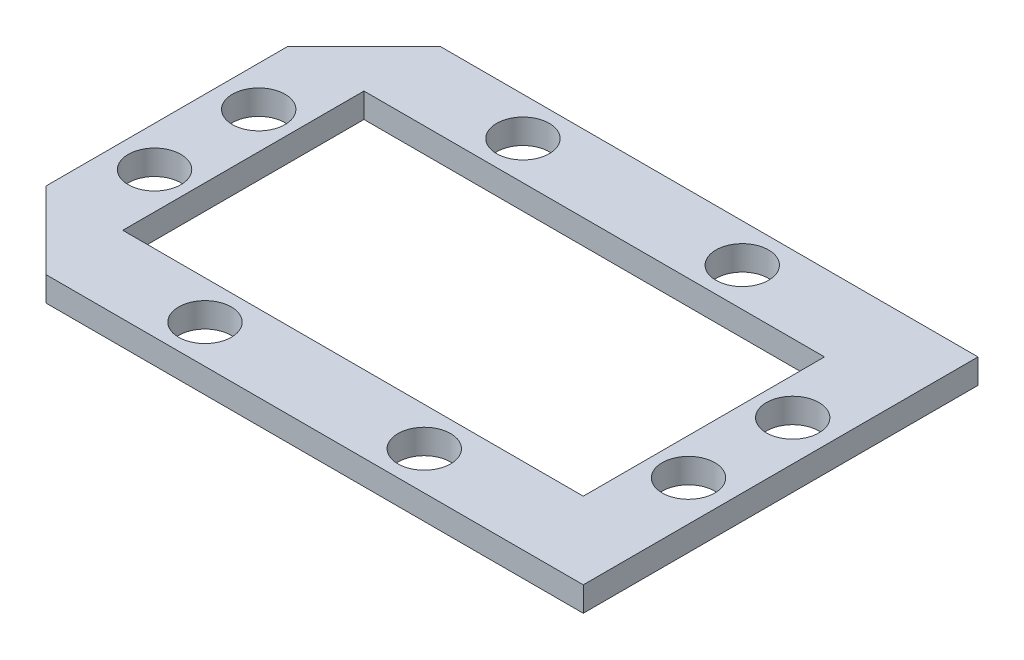
SolidWorks part; units mm, degrees
ref_plane "Front Plane" through (0, 0, 0) normal (0, 0, 1) x (1, 0, 0)
ref_plane "Top Plane" through (0, 0, 0) normal (0, 1, 0) x (1, 0, 0)
ref_plane "Right Plane" through (0, 0, 0) normal (1, 0, 0) x (0, 0, -1)
sketch "Sketch1" plane through (0, 0, 0) normal (0, 1, 0) x (1, 0, 0)
  line L0 (-24.35, 0) -> (24.35, 0) construction
  line L6 (-28, 18) -> (28, 18)
  line L7 (-21, 11) -> (21, 11)
  line L8 (-21, 11) -> (-21, -11)
  line L9 (-21, -11) -> (21, -11)
  line L10 (21, 11) -> (21, -11)
  line L11 (-21, 11) -> (21, -11) construction
  line L12 (-21, -11) -> (21, 11) construction
  line L13 (-24.35, 9.5) -> (24.35, 9.5)
  line L14 (-24.35, 9.5) -> (-24.35, -9.5)
  line L15 (-24.35, -9.5) -> (24.35, -9.5)
  line L16 (24.35, 9.5) -> (24.35, -9.5)
  line L17 (-24.35, 9.5) -> (24.35, -9.5) construction
  line L18 (-24.35, -9.5) -> (24.35, 9.5) construction
  line L19 (0, 0) -> (0, 9.5) construction
  line L20 (0, 0) -> (0, -9.5) construction
  line L21 (-24.35, -4.75) -> (24.35, -4.75) construction
  line L22 (-28, 18) -> (-28, -18)
  line L23 (-28, -18) -> (28, -18)
  line L24 (24.35, 4.75) -> (-24.35, 4.75) construction
  line L25 (28, 18) -> (28, -18)
  line L26 (-28, 18) -> (28, -18) construction
  line L27 (-28, -18) -> (28, 18) construction
  line L28 (-10, 14.5) -> (10, 14.5)
  line L29 (-10, 14.5) -> (-10, -14.5)
  line L30 (-10, -14.5) -> (10, -14.5)
  line L31 (10, 14.5) -> (10, -14.5)
  line L32 (-10, 14.5) -> (10, -14.5) construction
  line L33 (-10, -14.5) -> (10, 14.5) construction
  circle A0 centre (24.35, -4.75) radius 2.4
  circle A1 centre (24.35, 4.75) radius 2.4
  circle A2 centre (-24.35, -4.75) radius 2.4
  circle A3 centre (-24.35, 4.75) radius 2.4
  circle A5 centre (10, 14.5) radius 2.4
  circle A6 centre (10, -14.5) radius 2.4
  circle A7 centre (-10, -14.5) radius 2.4
  circle A8 centre (-10, 14.5) radius 2.4
  point P0 (0, 0)
  point P1 (0, 0)
  point P6 (0, 0)
  point P8 (0, 0)
  point P24 (0, -4.75)
  point P31 (0, 0)
  point P38 (0, 4.75)
  dimension "D3" = 4.8
  dimension "D4" = 4.8
  dimension "D5" = 4.8
  dimension "D6" = 4.8
  dimension "D13" = 4.8
  dimension "D14" = 4.8
  dimension "D15" = 4.8
  dimension "D16" = 4.8
  dimension "D1" = 48.7
  dimension "D2" = 19
  dimension "D7" = 42
  dimension "D8" = 22
  dimension "D9" = 36
  dimension "D10" = 56
  dimension "D11" = 29
  dimension "D12" = 20
extrude "Boss-Extrude1" add sketch "Sketch1" along normal blind 2.25 contours L25 L6 L22 L23 A8 L28 A5 L31 L7 L10 L13 L16 A1 A0 L15 L9 A6 L30 A7 L29 L8 L14 A2 A3 | A3 L14 A2 L15 L8 L13 | A7 L30 A6 L31 L9 L29 | A8 L29 L7 L31 A5 L28 | A1 L16 L13 L10 L15 A0
sketch "Sketch2" plane through (0, 2.25, 0) normal (0, 1, 0) x (1, 0, 0)
  line L0 (-21, 18) -> (-28, 11)
  line L10 (-28, -11) -> (-21, -11)
  line L11 (-28, -11) -> (-28, -18)
  line L12 (-28, -18) -> (-21, -18)
  line L13 (-21, -11) -> (-21, -18)
  line L14 (-28, -11) -> (-21, -18) construction
  line L15 (-28, -18) -> (-21, -11) construction
  line L16 (-28, 18) -> (-28, -18) construction
  line L17 (-28, -18) -> (28, -18) construction
  line L18 (-28, 18) -> (28, 18) construction
  line L19 (-28, 18) -> (-21, 18)
  line L20 (-28, 18) -> (-28, 11)
  line L21 (-28, 11) -> (-21, 11)
  line L22 (-21, 18) -> (-21, 11)
  line L23 (-28, 18) -> (-21, 11) construction
  line L24 (-28, 11) -> (-21, 18) construction
  line L25 (-28, -11) -> (-21, -18)
  point P0 (-24.5, -14.5)
  point P11 (-24.5, 14.5)
  line M14 (28, 18) -> (-28, 18)
  line M15 (-28, 18) -> (-28, -18)
  line M16 (-28, -18) -> (28, -18)
extrude "Cut-Extrude1" cut sketch "Sketch2" against normal blind 2.25 from surface at 0 contours L0 M14 M15 | L25 M15 M16 starting at face at (10, 2.25, -12.1)
